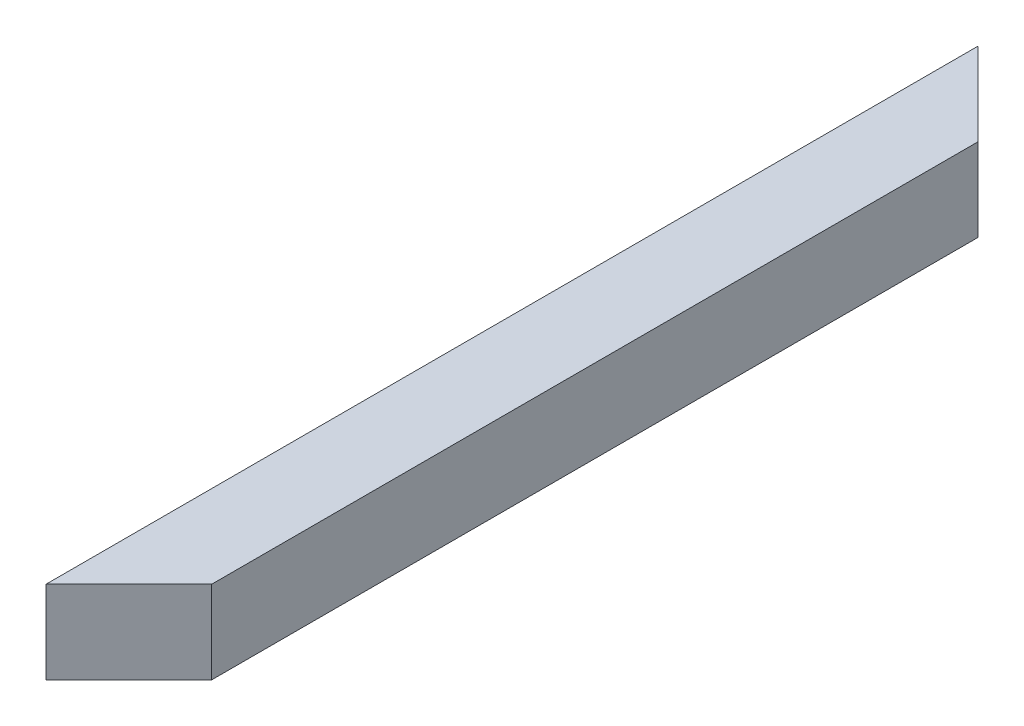
SolidWorks part; units mm, degrees
ref_plane "Front" through (0, 0, 0) normal (0, 0, 1) x (1, 0, 0)
ref_plane "Top" through (0, 0, 0) normal (0, 1, 0) x (1, 0, 0)
ref_plane "Right" through (0, 0, 0) normal (1, 0, 0) x (0, 0, -1)
sketch "Эскиз1" plane through (0, 0, 0) normal (0, 1, 0) x (1, 0, 0)
  line L0 (-177.8377, -16.8931) -> (-137.8377, 23.1069)
  line L2 (-177.8377, 433.1069) -> (-177.8377, -16.8931)
  line L4 (-137.8377, 393.1069) -> (-137.8377, 23.1069)
  line L5 (-177.8377, 433.1069) -> (-137.8377, 393.1069)
  dimension "D1" = 45
  dimension "D2" = 45
  dimension "D3" = 40
  dimension "D4" = 450
extrude "Бобышка-Вытянуть1" add sketch "Эскиз1" along normal blind 40
